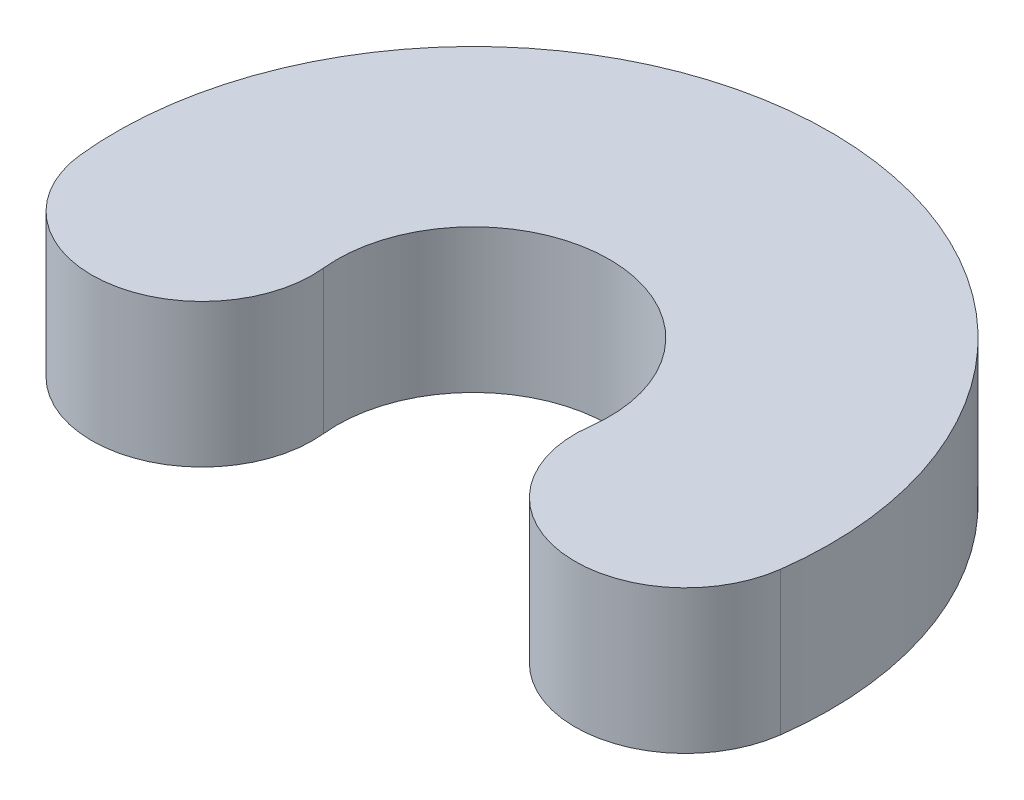
SolidWorks part; units mm, degrees
ref_plane "Front Plane" through (0, 0, 0) normal (0, 0, 1) x (1, 0, 0)
ref_plane "Top Plane" through (0, 0, 0) normal (0, 1, 0) x (1, 0, 0)
ref_plane "Right Plane" through (0, 0, 0) normal (1, 0, 0) x (0, 0, -1)
sketch "Sketch1" plane through (0, 0, 0) normal (0, 1, 0) x (1, 0, 0)
  arc A0 (56.2373, -7.4068) -> (-56.4101, -5.9489) centre (0, 0) ccw construction
  arc A1 (81.4198, -10.7235) -> (-81.67, -8.6127) centre (0, 0) ccw
  arc A2 (31.0547, -4.0901) -> (-31.1502, -3.285) centre (0, 0) ccw
  arc A3 (31.0547, -4.0901) -> (81.4198, -10.7235) centre (56.2373, -7.4068) ccw
  arc A4 (-81.67, -8.6127) -> (-31.1502, -3.285) centre (-56.4101, -5.9489) ccw
  point P3 (0.7341, 56.7182)
  point P8 (0, 0)
  dimension "D1" = 25.4
extrude "Boss-Extrude1" add sketch "Sketch1" along normal blind 33
shell "Shell1" thickness 10
